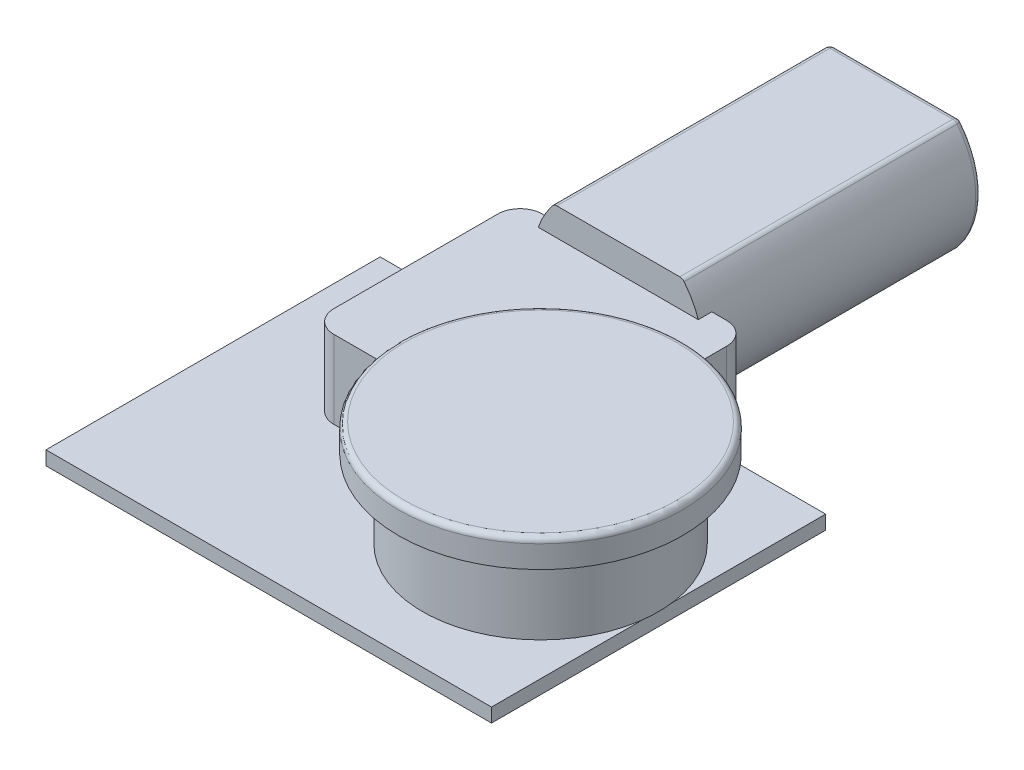
SolidWorks part; units mm, degrees
ref_plane "Front Plane" through (0, 0, 0) normal (0, 0, 1) x (1, 0, 0)
ref_plane "Top Plane" through (0, 0, 0) normal (0, 1, 0) x (1, 0, 0)
ref_plane "Right Plane" through (0, 0, 0) normal (1, 0, 0) x (0, 0, -1)
sketch "Sketch1" plane through (0, 0, 0) normal (0, 0, 1) x (1, 0, 0)
  line L1 (-14.605, -12.6229) -> (14.605, -12.6229)
  line L3 (-14.605, 12.6229) -> (14.605, 12.6229)
  line L5 (-14.605, -12.6229) -> (14.605, 12.6229) construction
  line L6 (-14.605, 12.6229) -> (14.605, -12.6229) construction
  arc A0 (-14.605, 12.6229) -> (-14.605, -12.6229) centre (0, 0) ccw
  arc A1 (14.605, -12.6229) -> (14.605, 12.6229) centre (0, 0) ccw
  dimension "D1" = 38.608
  dimension "D2" = 29.21
extrude "Boss-Extrude1" add sketch "Sketch1" along normal blind 63.5
sketch "Sketch2" plane through (0, 0, 0) normal (0, 0, -1) x (-1, 0, 0)
  circle A0 centre (0, 0) radius 6.985
  dimension "D1" = 13.97
extrude "Boss-Extrude2" add sketch "Sketch2" along normal blind 4.572
fillet "Fillet1" radius 1.27 10 edges at (-14.605, 12.6229, 31.75) (-6.985, 0, -4.572) (6.985, 0, 0) (14.605, -12.6229, 31.75) (0, -12.6229, 0) (-14.605, -12.6229, 31.75) (-19.304, 0, 0) (0, 12.6229, 0) (19.304, 0, 0) (14.605, 12.6229, 31.75)
sketch "Sketch3" plane through (0, 12.6229, 0) normal (0, 1, 0) x (1, 0, 0)
  line L0 (14.012, -63.5) -> (14.012, -107.95) construction
  line L1 (14.012, -107.95) -> (26.712, -107.95) construction
  circle A0 centre (26.712, -107.95) radius 32.385
  dimension "D3" = 64.77
  dimension "D1" = 44.45
  dimension "D2" = 12.7
extrude "Boss-Extrude3" add sketch "Sketch3" against normal blind 6.35 separate body
sketch "Sketch4" plane through (0, 6.2729, 0) normal (0, -1, 0) x (1, 0, 0)
  line L0 (26.712, 76.393) -> (26.712, 65.4918)
  line L1 (21.632, 60.4118) -> (13.5533, 60.4118)
  line L2 (-4.845, 107.95) -> (-20.4141, 107.95)
  line L3 (-25.4941, 102.87) -> (-25.4941, 65.4918)
  line L4 (-20.4141, 60.4118) -> (13.5533, 60.4118)
  arc A0 (30.9846, 81.4084) -> (0.1704, 112.2226) centre (26.712, 107.95) ccw
  arc A1 (-4.845, 107.95) -> (0.1704, 112.2226) centre (-4.845, 113.03) ccw
  arc A2 (26.712, 76.393) -> (30.9846, 81.4084) centre (31.792, 76.393) cw
  arc A3 (26.712, 65.4918) -> (21.632, 60.4118) centre (21.632, 65.4918) cw
  arc A4 (-25.4941, 65.4918) -> (-20.4141, 60.4118) centre (-20.4141, 65.4918) ccw
  arc A5 (-20.4141, 107.95) -> (-25.4941, 102.87) centre (-20.4141, 102.87) ccw
  point P10 (-0.1713, 107.95)
  point P13 (26.712, 81.0667)
  dimension "D1" = 5.08
extrude "Boss-Extrude4" add sketch "Sketch4" along normal blind 17.78 separate body
fillet "Fillet2" radius 1.27 1 edges at (26.712, 12.6229, 140.335)
sketch "Sketch5" plane through (0, -11.5071, 0) normal (0, -1, 0) x (1, 0, 0)
  circle A0 centre (26.712, 107.95) radius 6.35
  circle A1 centre (26.712, 107.95) radius 2.159
  dimension "D1" = 12.7
  dimension "D2" = 4.318
extrude "Boss-Extrude5" add sketch "Sketch5" along normal blind 6.35
sketch "Sketch6" plane through (0, -17.8571, 0) normal (0, -1, 0) x (1, 0, 0)
  line L0 (26.712, 107.95) -> (-54.568, 107.95) construction
  line L2 (-54.568, 63.2459) -> (47.032, 63.2459)
  line L3 (-54.568, 63.2459) -> (-54.568, 139.4459)
  line L4 (-54.568, 139.4459) -> (47.032, 139.4459)
  line L5 (47.032, 63.2459) -> (47.032, 139.4459)
  line L6 (-54.568, 63.2459) -> (47.032, 139.4459) construction
  line L7 (-54.568, 139.4459) -> (47.032, 63.2459) construction
  circle A0 centre (26.712, 107.95) radius 9.525
  point P8 (-3.768, 101.3459)
  dimension "D1" = 19.05
  dimension "D2" = 81.28
  dimension "D3" = 76.2
  dimension "D4" = 101.6
extrude "Boss-Extrude6" add sketch "Sketch6" along normal blind 3.175 separate body
